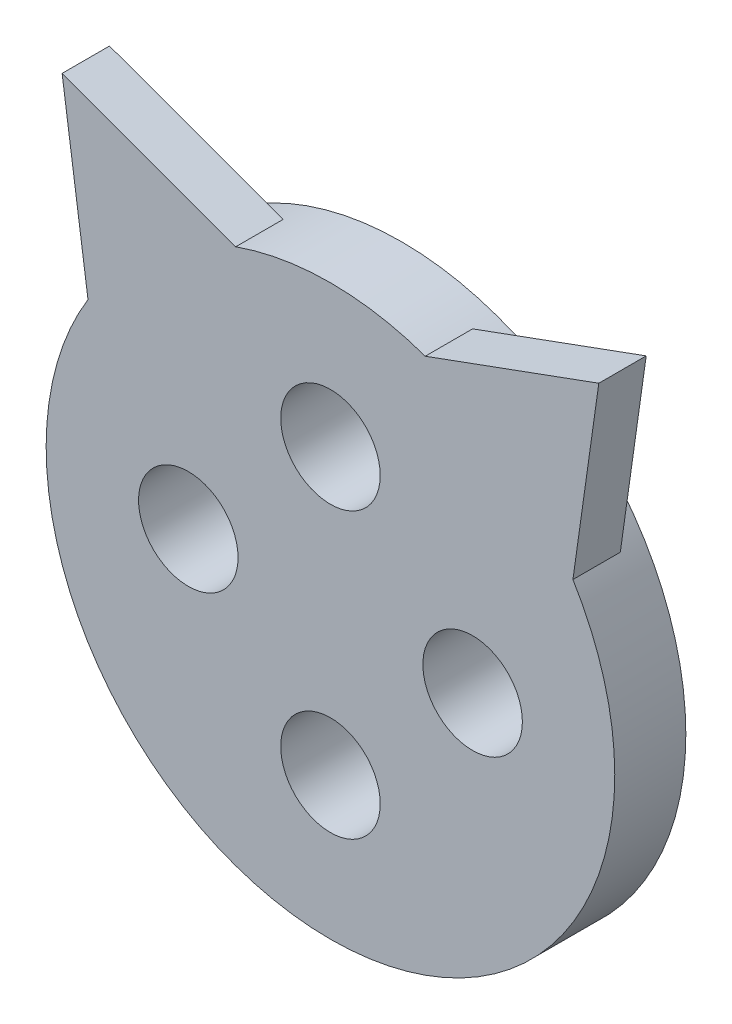
SolidWorks part; units mm, degrees
material "ABS"
ref_plane "前视基准面" through (0, 0, 0) normal (0, 0, 1) x (1, 0, 0)
ref_plane "上视基准面" through (0, 0, 0) normal (0, 1, 0) x (1, 0, 0)
ref_plane "右视基准面" through (0, 0, 0) normal (1, 0, 0) x (0, 0, -1)
other "Configuration Table"
sketch "草图1" plane through (0, 0, 0) normal (0, 0, 1) x (1, 0, 0)
  circle A0 centre (0, 0) radius 12
  circle A1 centre (0, 0) radius 6 construction
  circle A2 centre (0, 6) radius 2.1
  circle A4 centre (6, 0) radius 2.1
  circle A5 centre (0, -6) radius 2.1
  circle A6 centre (-6, 0) radius 2.1
  dimension "D1" = 24
  dimension "D2" = 12
  dimension "D3" = 4.2
  dimension "D4" = 4
extrude "凸台-拉伸1" add sketch "草图1" along normal blind 3
sketch "草图2" plane through (0, 0, 3) normal (0, 0, 1) x (1, 0, 0)
  line L0 (-10.2338, 6.2665) -> (-11.3267, 13.9895)
  line L1 (-11.3267, 13.9895) -> (-4, 11.3137)
  line L2 (0, -1000) -> (0, 49000) construction
  line L3 (10.2338, 6.2665) -> (11.3267, 13.9895)
  line L4 (11.3267, 13.9895) -> (4, 11.3137)
  circle A0 centre (0, 0) radius 12 construction
  arc A1 (-10.2338, 6.2665) -> (-4, 11.3137) centre (0, 0) cw
  arc A2 (10.2338, 6.2665) -> (4, 11.3137) centre (0, 0) ccw
  circle M7 centre (0, 0) radius 12
  dimension "D1" = 18
  dimension "D2" = 7.8
  dimension "D3" = 8
extrude "凸台-拉伸2" add sketch "草图2" against normal offset from surface (2 mm away) 1 contours L1 L0 M7 | L3 L4 M7 up to face at (12, 0, 0)
